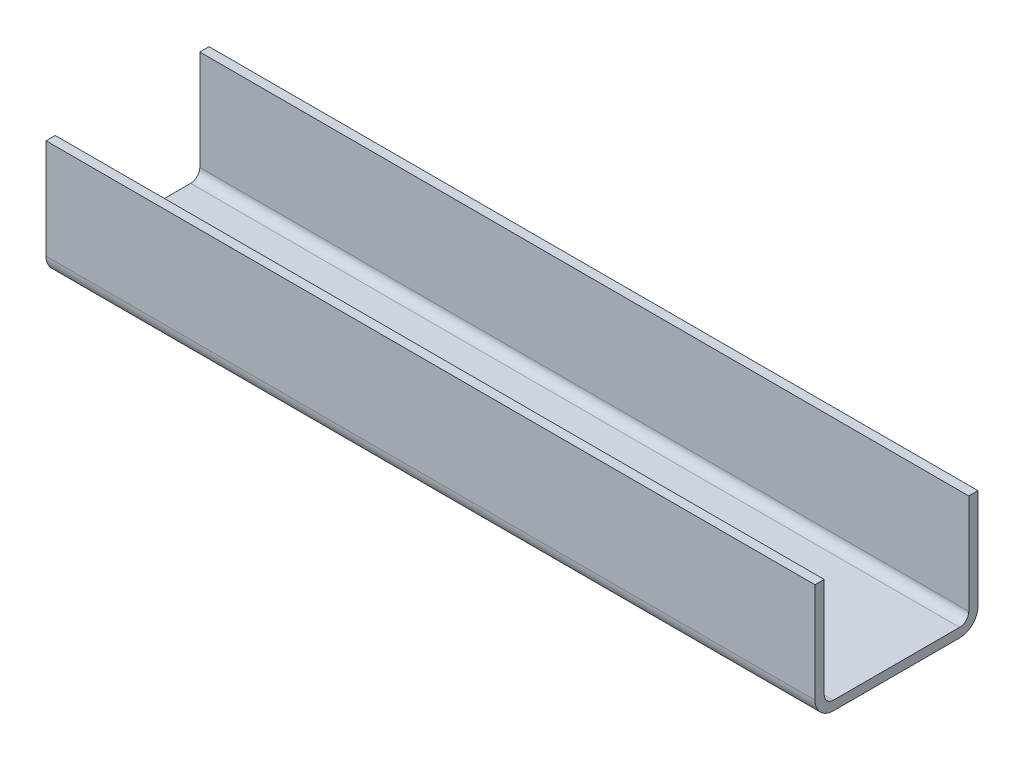
SolidWorks part; units mm, degrees
ref_plane "前视基准面" through (0, 0, 0) normal (0, 0, 1) x (1, 0, 0)
ref_plane "上视基准面" through (0, 0, 0) normal (0, 1, 0) x (1, 0, 0)
ref_plane "右视基准面" through (0, 0, 0) normal (1, 0, 0) x (0, 0, -1)
sketch "草图1" plane through (0, 0, 0) normal (1, 0, 0) x (0, 0, -1)
  line L0 (-25, 38.5) -> (-25, 6)
  line L1 (-20.5, 1.5) -> (20.5, 1.5)
  line L2 (25, 6) -> (25, 38.5)
  arc A0 (-25, 6) -> (-20.5, 1.5) centre (-20.5, 6) ccw
  arc A1 (20.5, 1.5) -> (25, 6) centre (20.5, 6) ccw
  point P8 (0, 1.5)
  dimension "BendRadius" = 4.5
  dimension "FloorWidth" = 41
  dimension "SideHeight" = 32.5
extrude "Track" add sketch "草图1" along normal mid plane 250 thin
